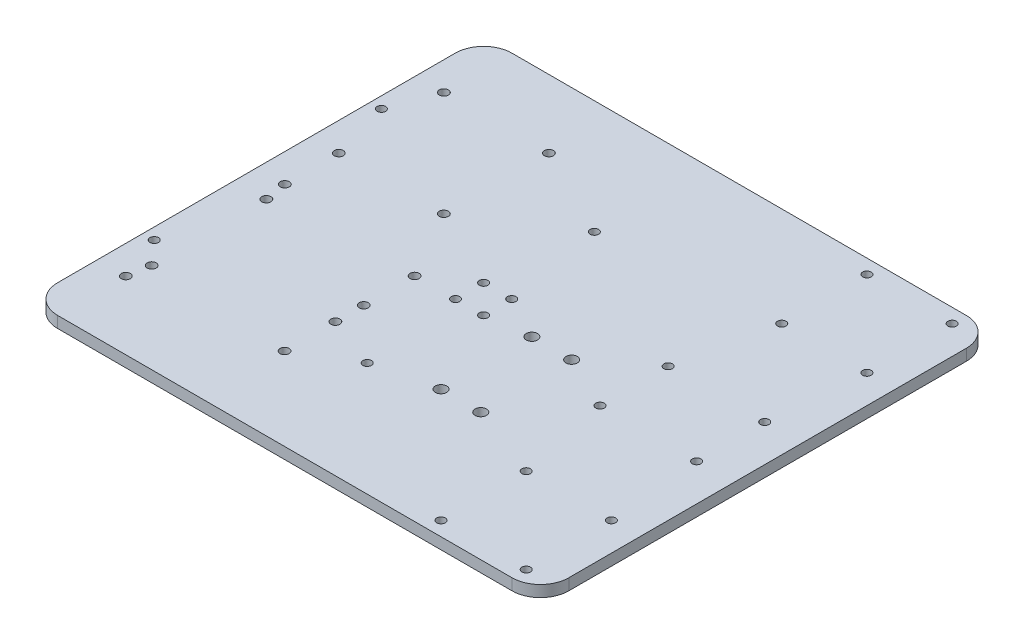
SolidWorks part; units mm, degrees
ref_plane "前视基准面" through (0, 0, 0) normal (0, 0, 1) x (1, 0, 0)
ref_plane "上视基准面" through (0, 0, 0) normal (0, 1, 0) x (1, 0, 0)
ref_plane "右视基准面" through (0, 0, 0) normal (1, 0, 0) x (0, 0, -1)
other "Configuration Table"
sketch "草图1" plane through (0, 0, 0) normal (0, 1, 0) x (1, 0, 0)
  line L1 (-90, -80) -> (90, -80)
  line L2 (-90, -80) -> (-90, 80)
  line L3 (-90, 80) -> (90, 80)
  line L4 (90, -80) -> (90, 80)
  line L5 (-90, -80) -> (90, 80) construction
  line L6 (-90, 80) -> (90, -80) construction
  point P0 (0, 0)
  dimension "D1" = 160
  dimension "D2" = 180
extrude "凸台-拉伸1" add sketch "草图1" along normal blind 4
sketch "草图2" plane through (0, 4, 0) normal (0, 1, 0) x (1, 0, 0)
  line L0 (90, -80) -> (90, 80) construction
  line L1 (66, -25) -> (85, -25) construction
  line L2 (66, -25) -> (66, 25) construction
  line L3 (66, 25) -> (85, 25) construction
  line L4 (85, -25) -> (85, 25) construction
  line L5 (66, -25) -> (85, 25) construction
  line L6 (66, 25) -> (85, -25) construction
  circle A0 centre (66, 25) radius 1.6
  circle A1 centre (66, -25) radius 1.6
  circle A2 centre (85, -25) radius 1.6
  circle A3 centre (85, 25) radius 1.6
  circle A7 centre (80.7, 7) radius 3
  point P0 (75.5, 0)
  dimension "D4" = 3.2
  dimension "D5" = 4.3
  dimension "D7" = 6
  dimension "D1" = 19
  dimension "D2" = 50
  dimension "D3" = 5
  dimension "D6" = 18
sketch "草图4" plane through (0, 4, 0) normal (0, 1, 0) x (1, 0, 0)
  line L0 (90, 80) -> (-90, 80) construction
  line L1 (-80, 56) -> (-43, 56) construction
  line L2 (-80, 56) -> (-80, 19) construction
  line L3 (-80, 19) -> (-43, 19) construction
  line L4 (-43, 56) -> (-43, 19) construction
  line L5 (-90, 80) -> (-90, -80) construction
  circle A0 centre (-80, 56) radius 1.6
  circle A1 centre (-43, 56) radius 1.6
  circle A2 centre (-43, 19) radius 1.6
  circle A3 centre (-80, 19) radius 1.6
  dimension "D4" = 3.2
  dimension "D1" = 37
  dimension "D2" = 24
  dimension "D3" = 10
extrude "切除-拉伸3" cut sketch "草图4" against normal blind 4
sketch "草图5" plane through (0, 4, 0) normal (0, 1, 0) x (1, 0, 0)
  line L0 (-90, -80) -> (90, -80) construction
  line L1 (-80, -56) -> (-29.2, -56) construction
  line L2 (-80, -56) -> (-80, -7.8) construction
  line L3 (-80, -7.8) -> (-29.2, -7.8) construction
  line L4 (-29.2, -56) -> (-29.2, -7.8) construction
  line L5 (-18.0867, -28) -> (49981.9133, -28) construction
  line L6 (-90, 80) -> (-90, -80) construction
  circle A0 centre (-78.7, -7.8) radius 1.6
  circle A1 centre (-29.2, -23) radius 1.6
  circle A2 centre (-29.2, -50.9) radius 1.6
  circle A3 centre (-80, -56) radius 1.6
  circle A4 centre (-29.2, -5.1) radius 1.6
  circle A5 centre (-29.2, -33) radius 1.6
  circle A6 centre (-80, 0) radius 1.6
  circle A7 centre (-78.7, -48.2) radius 1.6
  dimension "D8" = 3.2
  dimension "D1" = 48.2
  dimension "D2" = 50.8
  dimension "D3" = 24
  dimension "D4" = 10
  dimension "D5" = 1.3
  dimension "D6" = 15.2
  dimension "D7" = 27.9
  dimension "D9" = 52
extrude "切除-拉伸4" cut sketch "草图5" against normal blind 4
sketch "草图7" plane through (0, 0, 0) normal (0, -1, 0) x (1, 0, 0)
  line L0 (-90, 80) -> (90, 80) construction
  line L2 (90, 80) -> (90, -80) construction
  circle A0 centre (24, 35) radius 2
  circle A1 centre (10, 35) radius 2
  circle A2 centre (24, 3) radius 2
  circle A3 centre (10, 3) radius 2
  dimension "D2" = 4
  dimension "D5" = 4
  dimension "D1" = 80
  dimension "D3" = 45
  dimension "D6" = 14
  dimension "D7" = 32
extrude "切除-拉伸5" cut sketch "草图7" against normal blind 10
fillet "圆角1" radius 10 4 edges at (90, 2, 80) (90, 2, -80) (-90, 2, -80) (-90, 2, 80)
sketch "草图8" plane through (0, 0, 0) normal (0, -1, 0) x (1, 0, 0)
  line L1 (-14.9497, -4.9497) -> (-5.0503, -4.9497) construction
  line L2 (-14.9497, -4.9497) -> (-14.9497, 4.9497) construction
  line L3 (-14.9497, 4.9497) -> (-5.0503, 4.9497) construction
  line L4 (-5.0503, -4.9497) -> (-5.0503, 4.9497) construction
  line L5 (-14.9497, -4.9497) -> (-5.0503, 4.9497) construction
  line L6 (-14.9497, 4.9497) -> (-5.0503, -4.9497) construction
  circle A0 centre (-14.9497, 4.9497) radius 1.5
  circle A1 centre (-5.0503, 4.9497) radius 1.5
  circle A2 centre (-14.9497, -4.9497) radius 1.5
  circle A3 centre (-5.0503, -4.9497) radius 1.5
  point P0 (-10, 0)
  point P10 (-5.2248, 5.1183)
  dimension "D4" = 3
  dimension "D1" = 14
  dimension "D3" = 10
extrude "切除-拉伸6" cut sketch "草图8" against normal blind 10
sketch "草图11" plane through (0, 0, 0) normal (0, -1, 0) x (1, 0, 0)
  line L0 (60, 80) -> (60, -80) construction
  line L1 (-90, 0) -> (90, 0) construction
  line L2 (90, 70) -> (90, -70) construction
  line L3 (-90, -70) -> (-90, 70) construction
  line L4 (80, -80) -> (-80, -80) construction
  line L5 (-80, 80) -> (80, 80) construction
  circle A0 centre (77, 12) radius 1.5
  circle A1 centre (43, 12) radius 1.5
  circle A2 centre (77, -12) radius 1.5
  circle A3 centre (43, -12) radius 1.5
  dimension "D1" = 3
  dimension "D2" = 24
  dimension "D3" = 34
  dimension "D4" = 30
extrude "切除-拉伸8" cut sketch "草图11" against normal blind 4
sketch "草图12" plane through (0, 0, 0) normal (0, -1, 0) x (1, 0, 0)
  line L0 (-90, -70) -> (-90, 70) construction
  line L1 (-11, -40) -> (-86, -40) construction
  line L2 (-11, -40) -> (-11, 40) construction
  line L3 (-11, 40) -> (-86, 40) construction
  line L4 (-86, -40) -> (-86, 40) construction
  line L5 (-11, -40) -> (-86, 40) construction
  line L6 (-11, 40) -> (-86, -40) construction
  circle A0 centre (-86, 40) radius 1.5
  circle A1 centre (-11, 40) radius 1.5
  circle A2 centre (-11, -40) radius 1.5
  circle A3 centre (-86, -40) radius 1.5
  point P0 (-48.5, 0)
  dimension "D4" = 3
  dimension "D1" = 4
  dimension "D2" = 75
  dimension "D3" = 80
extrude "切除-拉伸9" cut sketch "草图12" against normal blind 4
sketch "草图13" plane through (0, 4, 0) normal (0, 1, 0) x (1, 0, 0)
  line L0 (80, 80) -> (-80, 80) construction
  line L1 (90, -70) -> (90, 70) construction
  circle A0 centre (80, 75) radius 1.5
  dimension "D2" = 3
  dimension "D1" = 5
  dimension "D3" = 10
extrude "切除-拉伸10" cut sketch "草图13" against normal blind 10
pattern_linear "阵列(线性)1" count 2 spacing 30 along (-1, 0, 0) count 2 spacing 30 along (0, 0, 1) of "切除-拉伸10"
mirror "镜向1" about plane through (0, 0, 0) normal (0, 0, 1) of "阵列(线性)1", "切除-拉伸10"
